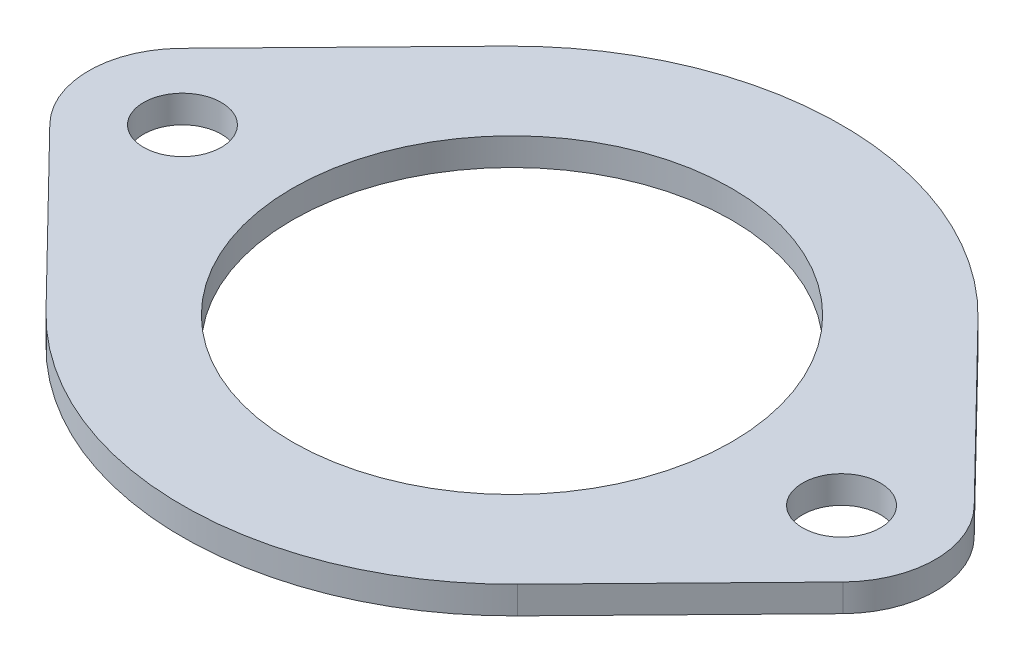
SolidWorks part; units mm, degrees
ref_plane "Front Plane" through (0, 0, 0) normal (0, 0, 1) x (1, 0, 0)
ref_plane "Top Plane" through (0, 0, 0) normal (0, 1, 0) x (1, 0, 0)
ref_plane "Right Plane" through (0, 0, 0) normal (1, 0, 0) x (0, 0, -1)
sketch "Sketch1" plane through (0, 0, 0) normal (0, 1, 0) x (1, 0, 0)
  line L0 (-22.9292, 3.7894) -> (-13.6271, 13.3118)
  line L1 (-22.9292, -3.7894) -> (-13.6271, -13.3118)
  line L2 (0, 0) -> (0, -8.3994) construction
  line L3 (22.9292, -3.7894) -> (13.6271, -13.3118)
  line L4 (22.9292, 3.7894) -> (13.6271, 13.3118)
  circle A0 centre (0, 0) radius 15.6845
  circle A1 centre (0, 0) radius 19.05 construction
  circle A2 centre (-19.05, 0) radius 2.2479
  circle A3 centre (19.05, 0) radius 2.2479
  arc A5 (-22.9292, 3.7894) -> (-22.9292, -3.7894) centre (-19.05, 0) ccw
  arc A6 (22.9292, -3.7894) -> (22.9292, 3.7894) centre (19.05, 0) ccw
  arc A7 (-13.6271, -13.3118) -> (13.6271, -13.3118) centre (0, 0) ccw
  arc A8 (13.6271, 13.3118) -> (-13.6271, 13.3118) centre (0, 0) ccw
  circle A9 centre (19.05, 0) radius 5.4229 construction
  circle A10 centre (-19.05, 0) radius 5.4229 construction
  dimension "D1" = 31.369
  dimension "D2" = 38.1
  dimension "D3" = 4.4958
  dimension "D4" = 3.175
  dimension "D5" = 38.1
extrude "Boss-Extrude1" add sketch "Sketch1" along normal blind 1.5875
sketch "Sketch2" plane through (0, 0, 0) normal (0, -1, 0) x (1, 0, 0)
  circle A1 centre (0, 0) radius 12.7
  circle A2 centre (0, 0) radius 15.6845 construction
  circle A3 centre (0, 0) radius 15.6845
  dimension "D1" = 25.4
extrude "Boss-Extrude2" add sketch "Sketch2" against normal blind 1.5875
